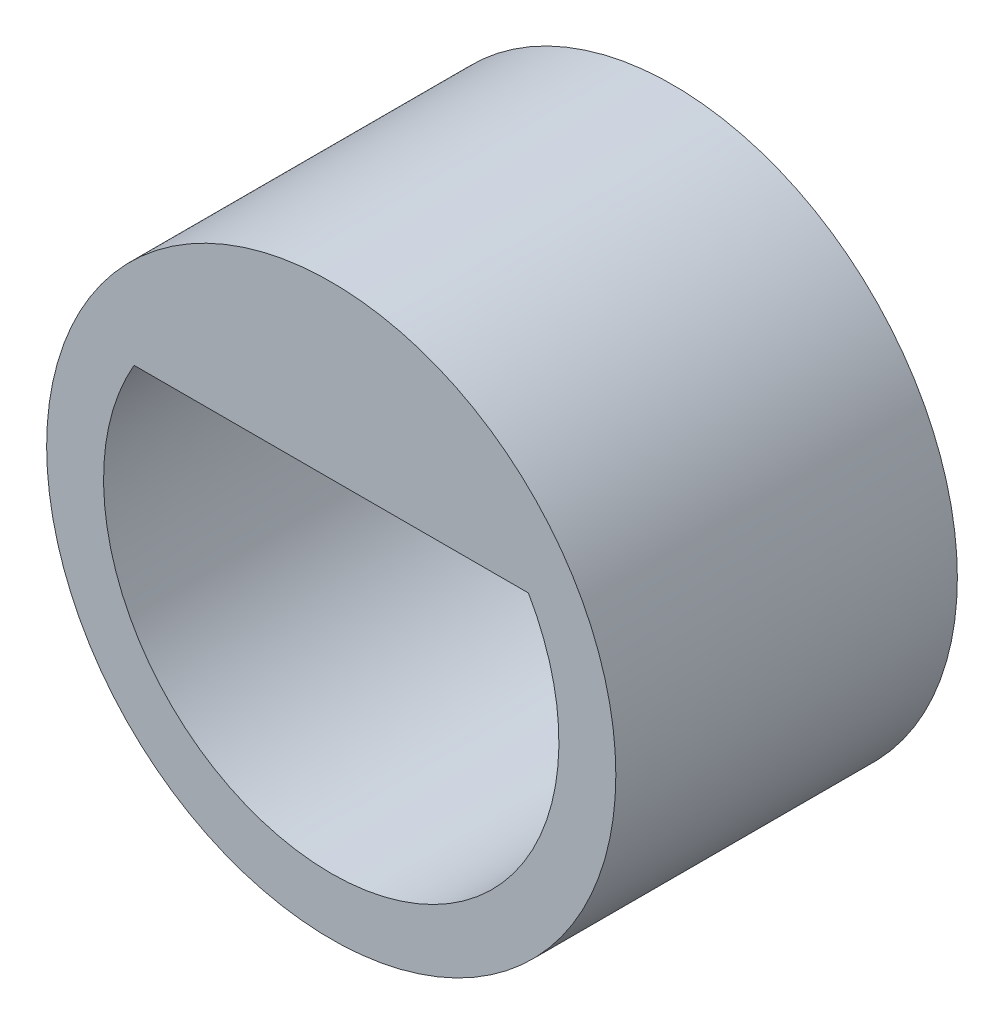
SolidWorks part; units mm, degrees
ref_plane "前视基准面" through (0, 0, 0) normal (0, 0, 1) x (1, 0, 0)
ref_plane "上视基准面" through (0, 0, 0) normal (0, 1, 0) x (1, 0, 0)
ref_plane "右视基准面" through (0, 0, 0) normal (1, 0, 0) x (0, 0, -1)
other "Configuration Table"
sketch "草图1" plane through (0, 0, 0) normal (0, 0, 1) x (1, 0, 0)
  line L0 (-2.2913, 1) -> (2.2913, 1)
  circle A0 centre (0, 0) radius 2.5
  circle A1 centre (0, 0) radius 2
  dimension "D1" = 5
  dimension "D2" = 4
  dimension "D3" = 1
extrude "凸台-拉伸1" add sketch "草图1" along normal blind 3 contours A1 L0 A0 | L0 A1 | A1 L0 A0
